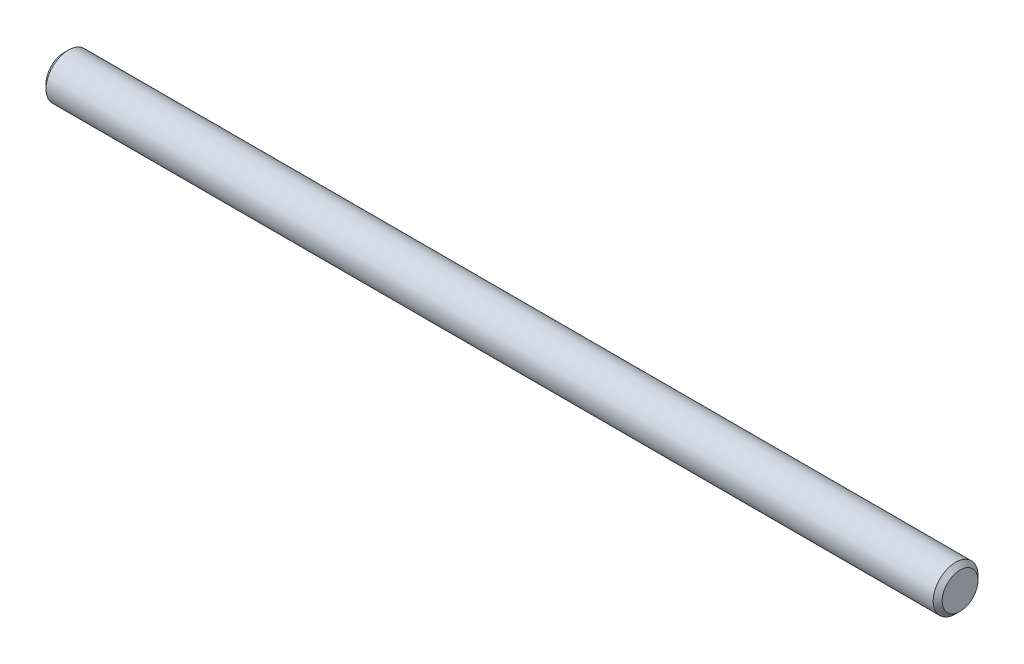
SolidWorks part; units mm, degrees
ref_plane "Front Plane" through (0, 0, 0) normal (0, 0, 1) x (1, 0, 0)
ref_plane "Top Plane" through (0, 0, 0) normal (0, 1, 0) x (1, 0, 0)
ref_plane "Right Plane" through (0, 0, 0) normal (1, 0, 0) x (0, 0, -1)
sketch "Sketch1" plane through (0, 0, 0) normal (0, 0, 1) x (1, 0, 0)
  line L0 (-7.9375, 0) -> (7.9375, 0) construction
  line L1 (-7.9375, 0.3969) -> (-7.9375, -0.3969) construction
  line L2 (7.9375, 0.3969) -> (7.9375, -0.3969) construction
  dimension "Diameter" = 0.7937
  dimension "Length" = 15.875
sketch "Sketch2" plane through (0, 0, 0) normal (1, 0, 0) x (0, 0, -1)
  circle A0 centre (0, 0) radius 0.3969
extrude "Extrude1" add sketch "Sketch2" against normal up to vertex (7.9375 mm away) and the other way up to vertex (7.9375 mm away) up to point (-7.9375, 0, 0) other way up to point (7.9375, 0, 0)
chamfer "Chamfer1" distance 0.0794 angle 45 2 edges at (7.9375, 0, -0.3969) (-7.9375, 0, -0.3969)
equation "\"D1@Chamfer1\" = \"Diameter@Sketch1\"*.1"
